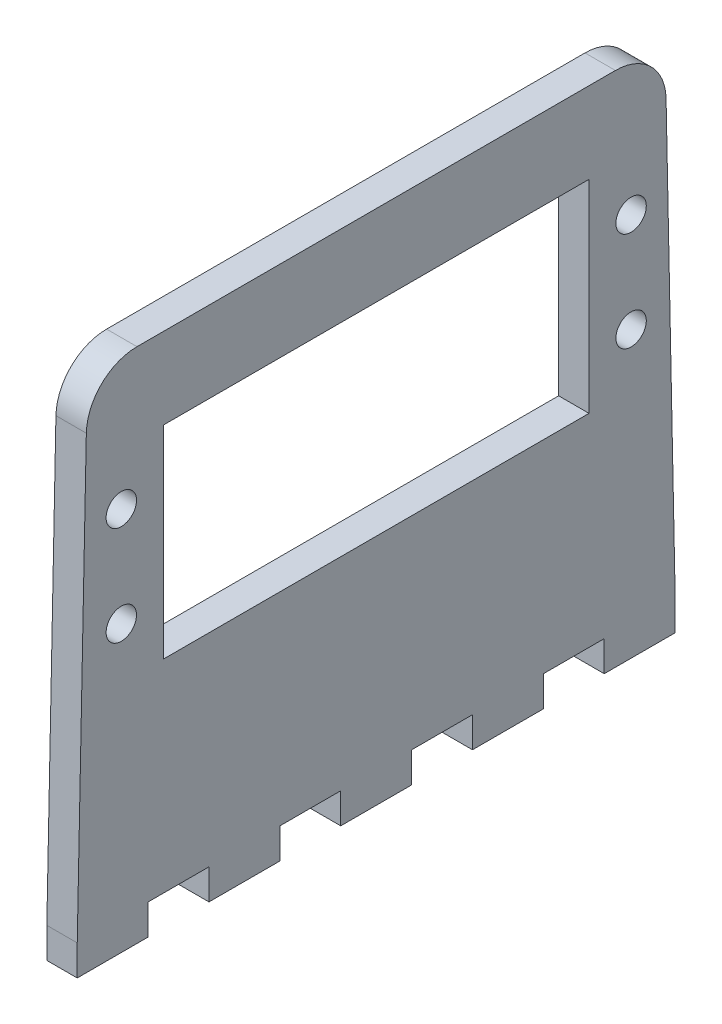
SolidWorks part; units mm, degrees
material "Perspex (TM) GS Acrylic Cast Sheet"
ref_plane "Front Plane" through (0, 0, 0) normal (0, 0, 1) x (1, 0, 0)
ref_plane "Top Plane" through (0, 0, 0) normal (0, 1, 0) x (1, 0, 0)
ref_plane "Right Plane" through (0, 0, 0) normal (1, 0, 0) x (0, 0, -1)
sketch "Sketch1" plane through (0, 0, 0) normal (1, 0, 0) x (0, 0, -1)
  line L0 (-33, 0) -> (-32, 48)
  line L1 (-32, 48) -> (25, 48)
  line L2 (25, 48) -> (26, 0)
  line L3 (26, 0) -> (26, -3)
  line L4 (26, -3) -> (19, -3)
  line L5 (19, -3) -> (19, 0)
  line L6 (19, 0) -> (13, 0)
  line L7 (13, 0) -> (13, -3)
  line L8 (13, -3) -> (6, -3)
  line L9 (6, -3) -> (6, 0)
  line L10 (6, 0) -> (0, 0)
  line L11 (0, 0) -> (0, -3)
  line L12 (0, -3) -> (-7, -3)
  line L13 (-7, -3) -> (-7, 0)
  line L14 (-7, 0) -> (-13, 0)
  line L15 (-13, 0) -> (-13, -3)
  line L16 (-13, -3) -> (-20, -3)
  line L17 (-20, -3) -> (-20, 0)
  line L18 (-20, 0) -> (-26, 0)
  line L19 (-26, 0) -> (-26, -3)
  line L20 (-26, -3) -> (-33, -3)
  line L21 (-33, -3) -> (-33, 0)
  line L22 (-3.5, 30) -> (-3.5, 35.1865) construction
  line L23 (-24.5, 40) -> (17.5, 40)
  line L24 (-24.5, 40) -> (-24.5, 20)
  line L25 (-24.5, 20) -> (17.5, 20)
  line L26 (17.5, 40) -> (17.5, 20)
  line L27 (-24.5, 40) -> (17.5, 20) construction
  line L28 (-24.5, 20) -> (17.5, 40) construction
  line L29 (-3.5, 30) -> (1.6461, 30) construction
  circle A0 centre (21.65, 34.9) radius 1.5
  circle A1 centre (21.65, 25.1) radius 1.5
  circle A2 centre (-28.65, 34.9) radius 1.5
  circle A3 centre (-28.65, 25.1) radius 1.5
  point P23 (-3.5, 30)
  point P38 (-3.5, -3)
  dimension "D7" = 20
  dimension "D8" = 3
  dimension "D1" = 7
  dimension "D2" = 3
  dimension "D3" = 6
  dimension "D4" = 20
  dimension "D5" = 42
  dimension "D6" = 8
  dimension "D9" = 5.1
  dimension "D10" = 4.15
  dimension "D12" = 57
extrude "Boss-Extrude1" add sketch "Sketch1" along normal blind 3
fillet "Fillet1" radius 5 2 edges at (1.5, 48, 32) (1.5, 48, -25)
